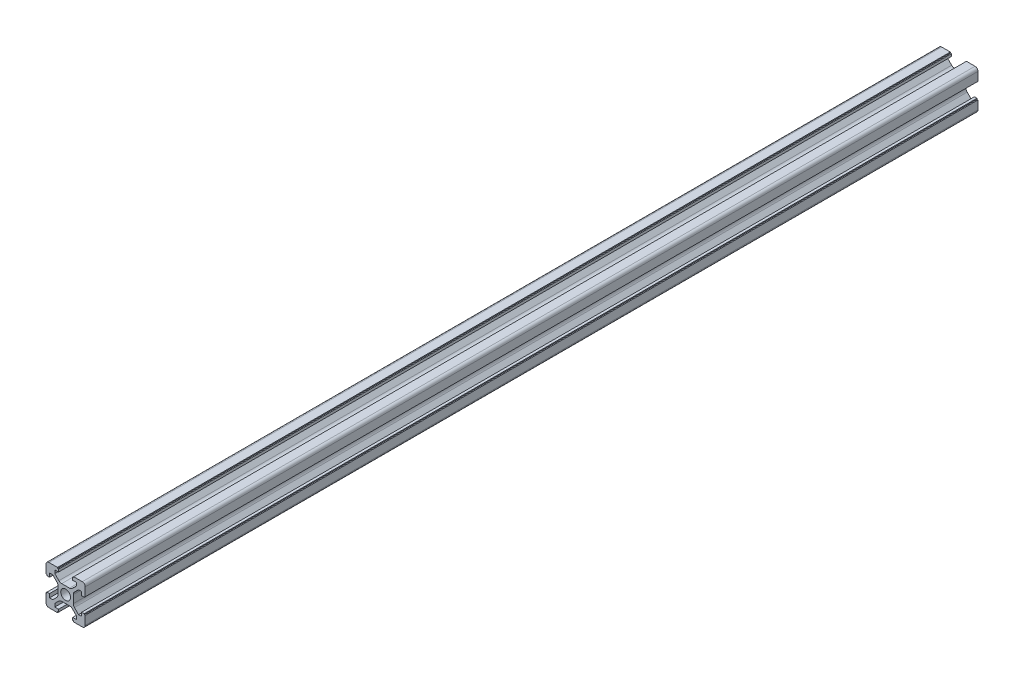
SolidWorks part; units mm, degrees
material "6063-O"
ref_plane "Front Plane" through (0, 0, 0) normal (0, 0, 1) x (1, 0, 0)
ref_plane "Top Plane" through (0, 0, 0) normal (0, 1, 0) x (1, 0, 0)
ref_plane "Right Plane" through (0, 0, 0) normal (1, 0, 0) x (0, 0, -1)
sketch "Sketch1" plane through (0, 0, 0) normal (0, 0, 1) x (1, 0, 0)
  line L0 (10, -4.1) -> (10, -8.5)
  line L1 (4.1, 10) -> (8.5, 10)
  line L2 (8.5, -10) -> (4.1, -10)
  line L3 (-8.5, -10) -> (-4.1, -10)
  line L4 (10, 8.5) -> (10, 4.1)
  line L7 (8.5, 10) -> (4.1, 10)
  line L8 (5.5, 6.5607) -> (3.4251, 4.4858)
  line L9 (8.5, 10) -> (4.1, 10)
  line L10 (3.9, 2.0109) -> (3.9, -2.0109)
  line L11 (2.0109, -3.9) -> (-2.0109, -3.9)
  line L12 (-3.9, -2.0109) -> (-3.9, 2.0109)
  line L13 (-2.0109, 3.9) -> (2.8393, 3.9)
  line L14 (2.5, 0) -> (22.2403, 0) construction
  line L15 (3.6, 9.5) -> (3.6, 8.2)
  line L16 (9.5, 3.6) -> (8.2, 3.6)
  line L17 (8.2, 3.6) -> (8.2, 5.5)
  line L18 (8.2, 5.5) -> (6.5607, 5.5)
  line L19 (10, -4.1) -> (10, -8.5)
  line L20 (4.1, 9.5) -> (3.6, 9.5)
  line L21 (4.1, 10) -> (4.1, 9.5)
  line L22 (8.5, 10) -> (4.1, 10)
  line L23 (10, 4.1) -> (9.5, 4.1)
  line L24 (9.5, 4.1) -> (9.5, 3.6)
  line L25 (5.5, 8.2) -> (5.5, 6.5607)
  line L26 (3.6, 8.2) -> (5.5, 8.2)
  line L27 (4.4858, 3.4251) -> (6.5607, 5.5)
  line L28 (10, -8.5) -> (10, -4.1)
  line L29 (6.5607, -5.5) -> (4.4858, -3.4251)
  line L30 (10, -8.5) -> (10, -4.1)
  line L31 (2.0109, -3.9) -> (-2.0109, -3.9)
  line L32 (3.9, 2.8393) -> (3.9, -2.0109)
  line L33 (9.5, -3.6) -> (8.2, -3.6)
  line L34 (3.6, -9.5) -> (3.6, -8.2)
  line L35 (3.6, -8.2) -> (5.5, -8.2)
  line L36 (5.5, -8.2) -> (5.5, -6.5607)
  line L37 (9.5, -4.1) -> (9.5, -3.6)
  line L38 (10, -4.1) -> (9.5, -4.1)
  line L39 (10, -8.5) -> (10, -4.1)
  line L40 (4.1, -10) -> (4.1, -9.5)
  line L41 (4.1, -9.5) -> (3.6, -9.5)
  line L42 (8.2, -5.5) -> (6.5607, -5.5)
  line L43 (8.2, -3.6) -> (8.2, -5.5)
  line L44 (3.4251, -4.4858) -> (5.5, -6.5607)
  line L45 (-4.1, -10) -> (-8.5, -10)
  line L46 (-10, -8.5) -> (-10, -4.1)
  line L47 (-8.5, -10) -> (-4.1, -10)
  line L48 (-5.5, -6.5607) -> (-3.4251, -4.4858)
  line L49 (-8.5, -10) -> (-4.1, -10)
  line L50 (-3.9, -2.0109) -> (-3.9, 2.0109)
  line L51 (2.0109, -3.9) -> (-2.0109, -3.9)
  line L52 (-3.6, -9.5) -> (-3.6, -8.2)
  line L53 (-9.5, -3.6) -> (-8.2, -3.6)
  line L54 (-8.2, -3.6) -> (-8.2, -5.5)
  line L55 (-8.2, -5.5) -> (-6.5607, -5.5)
  line L56 (-4.1, -9.5) -> (-3.6, -9.5)
  line L57 (-4.1, -10) -> (-4.1, -9.5)
  line L58 (-8.5, -10) -> (-4.1, -10)
  line L59 (-10, -4.1) -> (-9.5, -4.1)
  line L60 (-9.5, -4.1) -> (-9.5, -3.6)
  line L61 (-5.5, -8.2) -> (-5.5, -6.5607)
  line L62 (-3.6, -8.2) -> (-5.5, -8.2)
  line L63 (-4.4858, -3.4251) -> (-6.5607, -5.5)
  line L64 (-10, 4.1) -> (-10, 8.5)
  line L65 (-8.5, 10) -> (-4.1, 10)
  line L66 (-10, 8.5) -> (-10, 4.1)
  line L67 (-6.5607, 5.5) -> (-4.4858, 3.4251)
  line L68 (-10, 8.5) -> (-10, 4.1)
  line L69 (-2.0109, 3.9) -> (2.0109, 3.9)
  line L70 (-3.9, -2.0109) -> (-3.9, 2.0109)
  line L71 (-9.5, 3.6) -> (-8.2, 3.6)
  line L72 (-3.6, 9.5) -> (-3.6, 8.2)
  line L73 (-3.6, 8.2) -> (-5.5, 8.2)
  line L74 (-5.5, 8.2) -> (-5.5, 6.5607)
  line L75 (-9.5, 4.1) -> (-9.5, 3.6)
  line L76 (-10, 4.1) -> (-9.5, 4.1)
  line L77 (-10, 8.5) -> (-10, 4.1)
  line L78 (-4.1, 10) -> (-4.1, 9.5)
  line L79 (-4.1, 9.5) -> (-3.6, 9.5)
  line L80 (-8.2, 5.5) -> (-6.5607, 5.5)
  line L81 (-8.2, 3.6) -> (-8.2, 5.5)
  line L82 (-3.4251, 4.4858) -> (-5.5, 6.5607)
  line L83 (4.1, -10) -> (8.5, -10)
  arc A0 (2.0109, -3.9) -> (3.4251, -4.4858) centre (2.0109, -5.9) cw
  arc A1 (4.4858, -3.4251) -> (3.9, -2.0109) centre (5.9, -2.0109) cw
  arc A2 (3.9, 2.0109) -> (4.4858, 3.4251) centre (5.9, 2.0109) cw
  arc A3 (2.0109, 3.9) -> (3.4251, 4.4858) centre (2.0109, 5.9) ccw
  arc A4 (-2.0109, 3.9) -> (-3.4251, 4.4858) centre (-2.0109, 5.9) cw
  arc A5 (-4.4858, 3.4251) -> (-3.9, 2.0109) centre (-5.9, 2.0109) cw
  arc A6 (-3.4251, -4.4858) -> (-2.0109, -3.9) centre (-2.0109, -5.9) cw
  arc A7 (-3.9, -2.0109) -> (-4.4858, -3.4251) centre (-5.9, -2.0109) cw
  circle A8 centre (0, 0) radius 2.5
  arc A9 (-8.5, -10) -> (-10, -8.5) centre (-8.5, -8.5) cw
  arc A10 (-10, 8.5) -> (-8.5, 10) centre (-8.5, 8.5) cw
  arc A11 (8.5, 10) -> (10, 8.5) centre (8.5, 8.5) cw
  arc A12 (8.5, -10) -> (10, -8.5) centre (8.5, -8.5) ccw
  point P0 (0, 0)
  point P86 (0, 0)
  point P107 (10, -10)
  dimension "D3" = 2
  dimension "D5" = 5
  dimension "D2" = 1.5
  dimension "D8" = 1.5
  dimension "D6" = 4
  dimension "D7" = 6.1
  dimension "D11" = 0.5
  dimension "D12" = 0.5
extrude "Boss-Extrude2" add sketch "Sketch1" along normal blind 455
